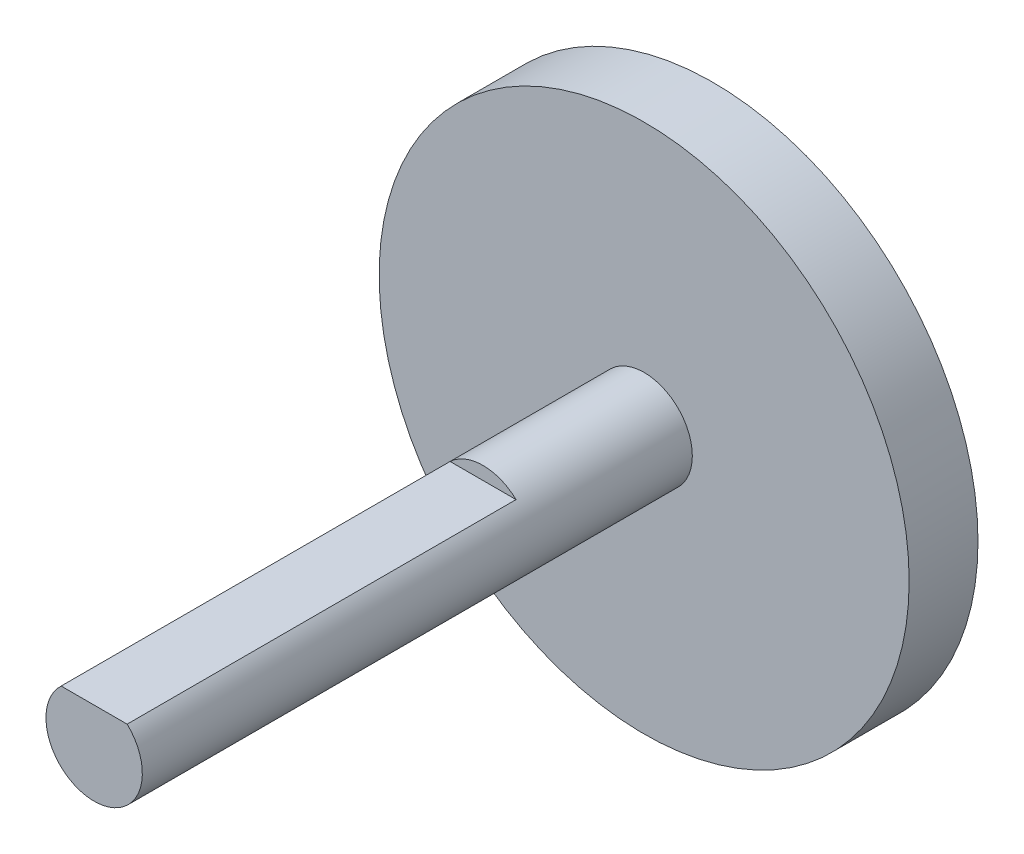
SolidWorks part; units mm, degrees
ref_plane "Alzado" through (0, 0, 0) normal (0, 0, 1) x (1, 0, 0)
ref_plane "Planta" through (0, 0, 0) normal (0, 1, 0) x (1, 0, 0)
ref_plane "Vista lateral" through (0, 0, 0) normal (1, 0, 0) x (0, 0, -1)
sketch "Croquis1" plane through (0, 0, 0) normal (0, 0, 1) x (1, 0, 0)
  circle A0 centre (0, 0) radius 19.25
  dimension "D1" = 38.5
extrude "Saliente-Extruir1" add sketch "Croquis1" along normal blind 5
sketch "Croquis2" plane through (0, 0, 5) normal (0, 0, 1) x (1, 0, 0)
  circle A0 centre (0, 0) radius 3.5
  dimension "D1" = 7
extrude "Saliente-Extruir2" add sketch "Croquis2" along normal blind 11.7
sketch "Croquis3" plane through (0, 0, 16.7) normal (0, 0, 1) x (1, 0, 0)
  line L0 (-2.3974, 2.55) -> (2.3974, 2.55)
  line L1 (0, -3.5) -> (0, 2.55) construction
  circle A0 centre (0, 0) radius 3.5 construction
  arc A1 (-2.3974, 2.55) -> (2.3974, 2.55) centre (0, 0) ccw
  dimension "D1" = 6.05
extrude "Saliente-Extruir3" add sketch "Croquis3" along normal blind 28.25
